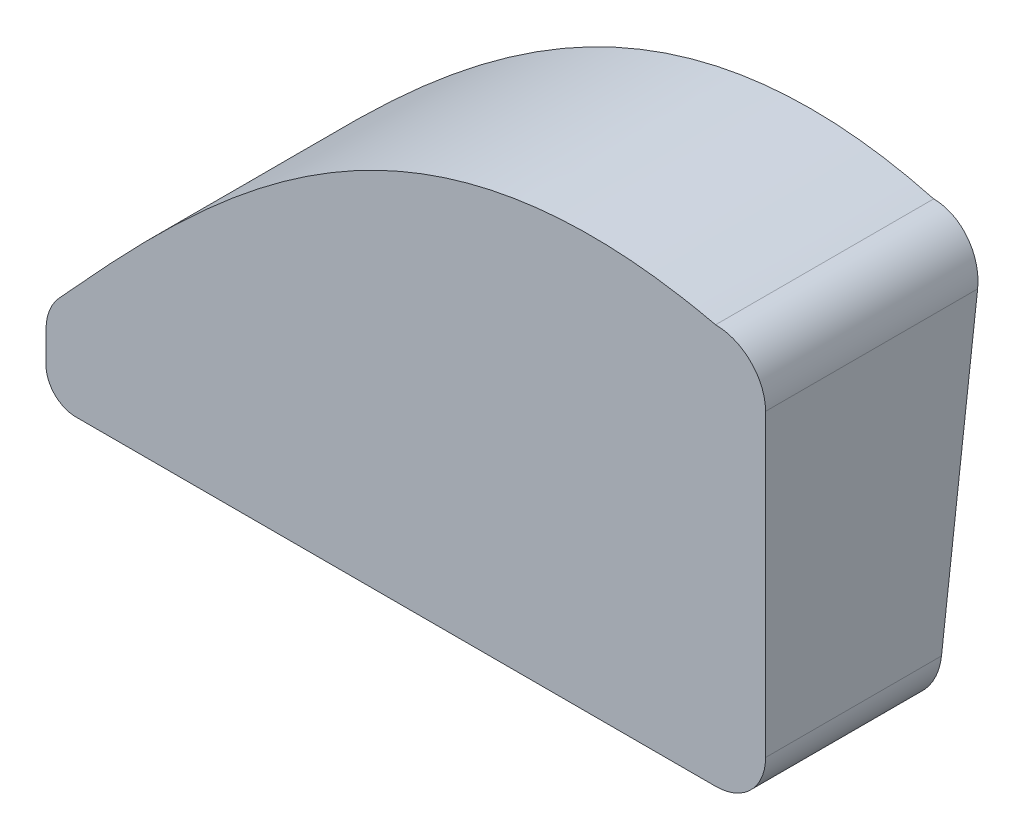
SolidWorks part; units mm, degrees
ref_plane "Front Plane" through (0, 0, 0) normal (0, 0, 1) x (1, 0, 0)
ref_plane "Top Plane" through (0, 0, 0) normal (0, 1, 0) x (1, 0, 0)
ref_plane "Right Plane" through (0, 0, 0) normal (1, 0, 0) x (0, 0, -1)
sketch "Sketch1" plane through (0, 0, 0) normal (0, 0, 1) x (1, 0, 0)
  line L2 (54.303, 17.599) -> (54.303, -12.3967)
  line L3 (49.303, -17.3967) -> (-14.6956, -17.3967)
  line L4 (-17.6956, -11.3067) -> (-17.6956, -14.3967)
  arc A0 (54.303, 17.599) -> (49.303, 22.599) centre (49.303, 17.599) ccw
  arc A1 (49.303, -17.3967) -> (54.303, -12.3967) centre (49.303, -12.3967) ccw
  arc A2 (-17.6956, -11.3067) -> (-16.3915, -7.9392) centre (-12.6956, -11.3067) cw
  arc A3 (-14.6956, -17.3967) -> (-17.6956, -14.3967) centre (-14.6956, -14.3967) cw
  spline S0 degree 3 poles (-16.3915, -7.9392) (-0.1359, 9.9015) (18.6969, 29.7257) (49.303, 22.599) knots 0.0263 0.0263 0.0263 0.0263 1 1 1 1
  point P1 (-17.6956, -17.3967)
  point P5 (0, 0)
  point P6 (-17.6956, -9.3967)
  point P9 (-17.697, -17.3967)
  point P10 (-15.897, -7.3967)
  point P13 (54.303, 22.599)
  point P18 (-17.4619, -17.4245)
  point P20 (-17.6956, -17.3967)
  dimension "D4" = 5
  dimension "D7" = 5
  dimension "D2" = 5
  dimension "D1" = 3
  dimension "D3" = 5
  dimension "D5" = 8
  dimension "D6" = 10
extrude "Boss-Extrude1" add sketch "Sketch1" along normal blind 22 contours A0 S0 A2 L4 A3 L3 A1 L2
sketch "Sketch3" plane through (0, 0, 0) normal (1, 0, 0) x (0, 0, -1)
  line L0 (0, 24.0876) -> (-5, -17.3967)
  line L1 (-22, -17.3967) -> (0, -17.3967) construction
  dimension "D1" = 5
extrude "Cut-Extrude3" cut sketch "Sketch3" against normal through all and the other way through all
